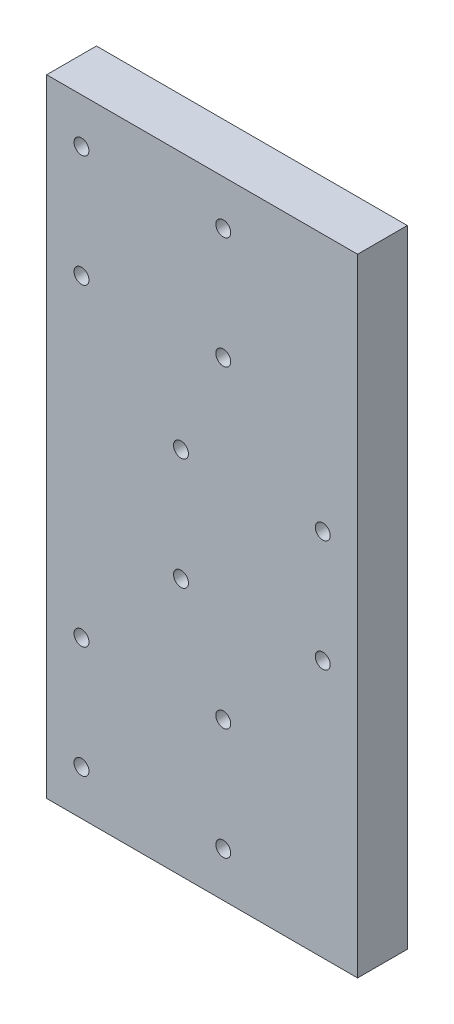
SolidWorks part; units mm, degrees
ref_plane "Piano frontale" through (0, 0, 0) normal (0, 0, 1) x (1, 0, 0)
ref_plane "Piano superiore" through (0, 0, 0) normal (0, 1, 0) x (1, 0, 0)
ref_plane "Piano destro" through (0, 0, 0) normal (1, 0, 0) x (0, 0, -1)
sketch "Schizzo1" plane through (0, 0, 0) normal (0, 0, 1) x (1, 0, 0)
  line L0 (60, 126) -> (60, -126)
  line L1 (60, -126) -> (-65, -126)
  line L3 (60, 126) -> (-60, 126)
  line L4 (-60, 126) -> (-65, 126)
  line L5 (60, -126) -> (-60, 126) construction
  line L6 (60, 126) -> (-60, -126) construction
  line L9 (-65, 126) -> (-65, -126)
  point P1 (0, 0)
  dimension "D1" = 125
  dimension "D2" = 252
extrude "Estrusione-Estrusione1" add sketch "Schizzo1" along normal blind 20
sketch "Schizzo4" plane through (0, 0, 0) normal (0, 0, -1) x (-1, 0, 0)
  circle A0 centre (-6, -108) radius 3 construction
  circle A1 centre (-6, -63) radius 3 construction
  circle A2 centre (51, -108) radius 3 construction
  circle A3 centre (51, -63) radius 3 construction
  circle A4 centre (-6, -108) radius 3
  circle A5 centre (-6, -63) radius 3
  circle A6 centre (51, -108) radius 3
  circle A7 centre (51, -63) radius 3
  circle A8 centre (11, -22.5) radius 3 construction
  circle A9 centre (11, 22.5) radius 3 construction
  circle A10 centre (11, -22.5) radius 3
  circle A11 centre (11, 22.5) radius 3
  circle A12 centre (-46, -22.5) radius 3 construction
  circle A13 centre (-46, 22.5) radius 3 construction
  circle A14 centre (-46, -22.5) radius 3
  circle A15 centre (-46, 22.5) radius 3
  circle A16 centre (51, 63) radius 3 construction
  circle A17 centre (51, 108) radius 3 construction
  circle A18 centre (51, 63) radius 3
  circle A19 centre (51, 108) radius 3
  circle A20 centre (-6, 63) radius 3 construction
  circle A21 centre (-6, 108) radius 3 construction
  circle A22 centre (-6, 63) radius 3
  circle A23 centre (-6, 108) radius 3
sketch "Schizzo5" plane through (0, 0, 0) normal (0, 0, -1) x (-1, 0, 0)
  circle A0 centre (51, 108) radius 3 construction
  circle A1 centre (51, 63) radius 3 construction
  circle A2 centre (-6, 108) radius 3 construction
  circle A3 centre (-6, 63) radius 3 construction
  circle A4 centre (11, 22.5) radius 3 construction
  circle A5 centre (11, -22.5) radius 3 construction
  circle A6 centre (-46, 22.5) radius 3 construction
  circle A7 centre (-46, -22.5) radius 3 construction
  circle A8 centre (-6, -63) radius 3 construction
  circle A9 centre (-6, -108) radius 3 construction
  circle A10 centre (51, -63) radius 3 construction
  circle A11 centre (51, -108) radius 3 construction
  circle A12 centre (51, 108) radius 3
  circle A13 centre (51, 63) radius 3
  circle A14 centre (-6, 108) radius 3
  circle A15 centre (-6, 63) radius 3
  circle A16 centre (11, 22.5) radius 3
  circle A17 centre (11, -22.5) radius 3
  circle A18 centre (-46, 22.5) radius 3
  circle A19 centre (-46, -22.5) radius 3
  circle A20 centre (-6, -63) radius 3
  circle A21 centre (-6, -108) radius 3
  circle A22 centre (51, -63) radius 3
  circle A23 centre (51, -108) radius 3
extrude "Taglio-Estrusione1" cut sketch "Schizzo5" against normal through all
